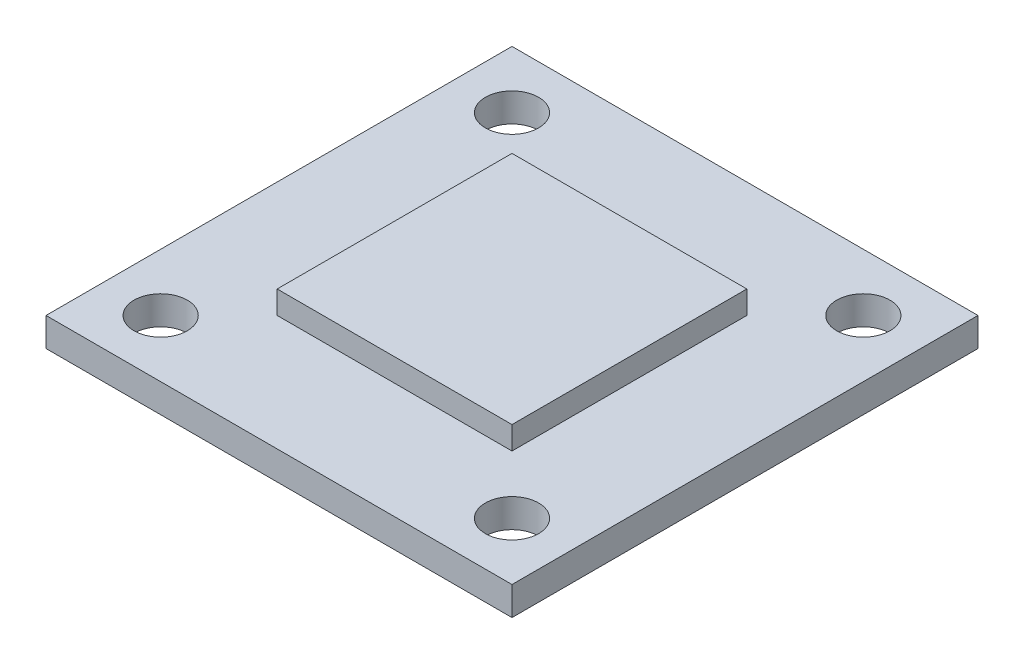
SolidWorks part; units mm, degrees
ref_plane "Front Plane" through (0, 0, 0) normal (0, 0, 1) x (1, 0, 0)
ref_plane "Top Plane" through (0, 0, 0) normal (0, 1, 0) x (1, 0, 0)
ref_plane "Right Plane" through (0, 0, 0) normal (1, 0, 0) x (0, 0, -1)
sketch "Sketch1" plane through (0, 0, 0) normal (0, 1, 0) x (1, 0, 0)
  line L1 (-12.9032, -12.9032) -> (12.9032, -12.9032)
  line L2 (-12.9032, -12.9032) -> (-12.9032, 12.9032)
  line L3 (-12.9032, 12.9032) -> (12.9032, 12.9032)
  line L4 (12.9032, -12.9032) -> (12.9032, 12.9032)
  line L5 (-12.9032, -12.9032) -> (12.9032, 12.9032) construction
  line L6 (-12.9032, 12.9032) -> (12.9032, -12.9032) construction
  point P0 (0, 0)
  dimension "D1" = 25.8064
  dimension "D2" = 25.8064
extrude "Boss-Extrude1" add sketch "Sketch1" along normal blind 1.5875
sketch "Sketch2" plane through (0, 1.5875, 0) normal (0, 1, 0) x (1, 0, 0)
  line L1 (-6.5024, -6.5024) -> (6.5024, -6.5024)
  line L2 (-6.5024, -6.5024) -> (-6.5024, 6.5024)
  line L3 (-6.5024, 6.5024) -> (6.5024, 6.5024)
  line L4 (6.5024, -6.5024) -> (6.5024, 6.5024)
  line L5 (-6.5024, -6.5024) -> (6.5024, 6.5024) construction
  line L6 (-6.5024, 6.5024) -> (6.5024, -6.5024) construction
  point P0 (0, 0)
  dimension "D1" = 13.0048
  dimension "D2" = 13.0048
extrude "Boss-Extrude2" add sketch "Sketch2" along normal blind 1.27
sketch "Sketch3" plane through (0, 1.5875, 0) normal (0, 1, 0) x (1, 0, 0)
  line L5 (-9.7282, -9.7282) -> (9.7282, 9.7282) construction
  line L6 (-9.7282, 9.7282) -> (9.7282, -9.7282) construction
  point P0 (0, 0)
  point P7 (-9.7282, 9.7282)
  point P8 (9.7282, 9.7282)
  point P9 (9.7282, -9.7282)
  point P10 (-9.7282, -9.7282)
  dimension "D1" = 19.4564
  dimension "D2" = 19.4564
hole_wizard "#32 (0.116) Diameter Hole1" positions "3DSketch1" profile "Sketch4" hole size "#32" standard "ANSI Inch" end condition through all
sketch3d "3DSketch1"
  point P0 (-9.7282, 1.5875, -9.7282)
  point P3 (-9.7282, 1.5875, 9.7282)
  point P6 (9.7282, 1.5875, 9.7282)
  point P9 (9.7282, 1.5875, -9.7282)
sketch "Sketch4" plane through (-9.7282, 1.5875, -9.7282) normal (1, 0, 0) x (0, 0, 1)
  line L0 (0, 0) -> (0, 1.5875)
  line L1 (0, 1.5875) -> (1.4732, 1.5875)
  line L2 (1.4732, 1.5875) -> (1.4732, 0)
  line L5 (1.4732, 0) -> (0, 0)
  line L11 (0, -6.35) -> (0, 107.95) construction
  dimension "Thru Hole Dia." = 2.9464
  dimension "Thru Hole Depth" = 1.5875
